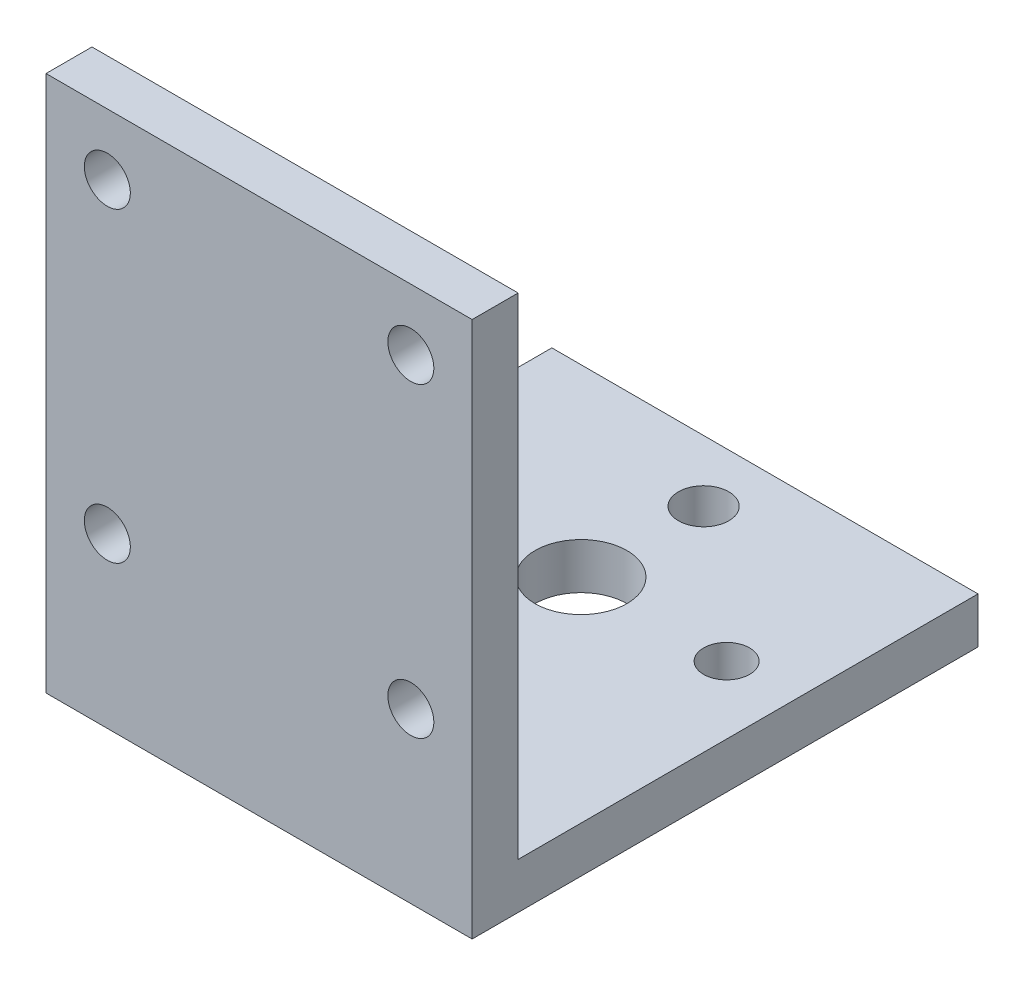
SolidWorks part; units mm, degrees
ref_plane "Front Plane" through (0, 0, 0) normal (0, 0, 1) x (1, 0, 0)
ref_plane "Top Plane" through (0, 0, 0) normal (0, 1, 0) x (1, 0, 0)
ref_plane "Right Plane" through (0, 0, 0) normal (1, 0, 0) x (0, 0, -1)
sketch "Sketch1" plane through (0, 0, 0) normal (0, 1, 0) x (1, 0, 0)
  line L1 (-77.7121, 11.7707) -> (-49.9121, 11.7707)
  line L2 (-77.7121, 11.7707) -> (-77.7121, -21.2293)
  line L3 (-77.7121, -21.2293) -> (-49.9121, -21.2293)
  line L4 (-49.9121, 11.7707) -> (-49.9121, -21.2293)
  circle A0 centre (-63.8121, 7.7707) radius 1.6431
  circle A1 centre (-63.8121, -0.2293) radius 3
  circle A2 centre (-63.8121, -8.2293) radius 1.5
  circle A3 centre (-73.3121, -0.2293) radius 1.5
  circle A4 centre (-54.3121, -0.2293) radius 1.5
  dimension "D1" = 13.9
  dimension "D3" = 8
  dimension "D4" = 8
  dimension "D5" = 13
  dimension "D6" = 9.5
  dimension "D7" = 9.5
  dimension "D2" = 4
extrude "Boss-Extrude2" add sketch "Sketch1" along normal blind 3
sketch "Sketch2" plane through (0, 3, 0) normal (0, 1, 0) x (1, 0, 0)
  line L0 (-77.7121, 11.7707) -> (-77.7121, -21.2293) construction
  line L1 (-77.7121, -18.2293) -> (-49.9121, -18.2293)
  line L2 (-77.7121, -18.2293) -> (-77.7121, -21.2293)
  line L3 (-77.7121, -21.2293) -> (-49.9121, -21.2293)
  line L4 (-49.9121, -18.2293) -> (-49.9121, -21.2293)
  line L5 (-77.7121, -21.2293) -> (-49.9121, -21.2293) construction
  point P4 (-77.7121, -21.2293)
extrude "Boss-Extrude4" add sketch "Sketch2" along normal blind 32
sketch "Sketch4" plane through (0, 0, 18.2293) normal (0, 0, -1) x (-1, 0, 0)
  line L0 (49.9121, 35) -> (77.7121, 35) construction
  line L1 (49.9121, 35) -> (49.9121, 3) construction
  line L2 (77.7121, 35) -> (77.7121, 3) construction
  line L3 (49.9121, 3) -> (77.7121, 3) construction
  circle A0 centre (53.9121, 31) radius 1.5
  circle A1 centre (73.7121, 31) radius 1.5
  circle A2 centre (53.9121, 11) radius 1.5
  circle A3 centre (73.7121, 11) radius 1.5
  dimension "D1" = 4
  dimension "D3" = 4
  dimension "D5" = 8
  dimension "D2" = 4
  dimension "D4" = 4
extrude "Cut-Extrude2" cut sketch "Sketch4" against normal blind 32 contours A2 | A1 | A0 | A3
